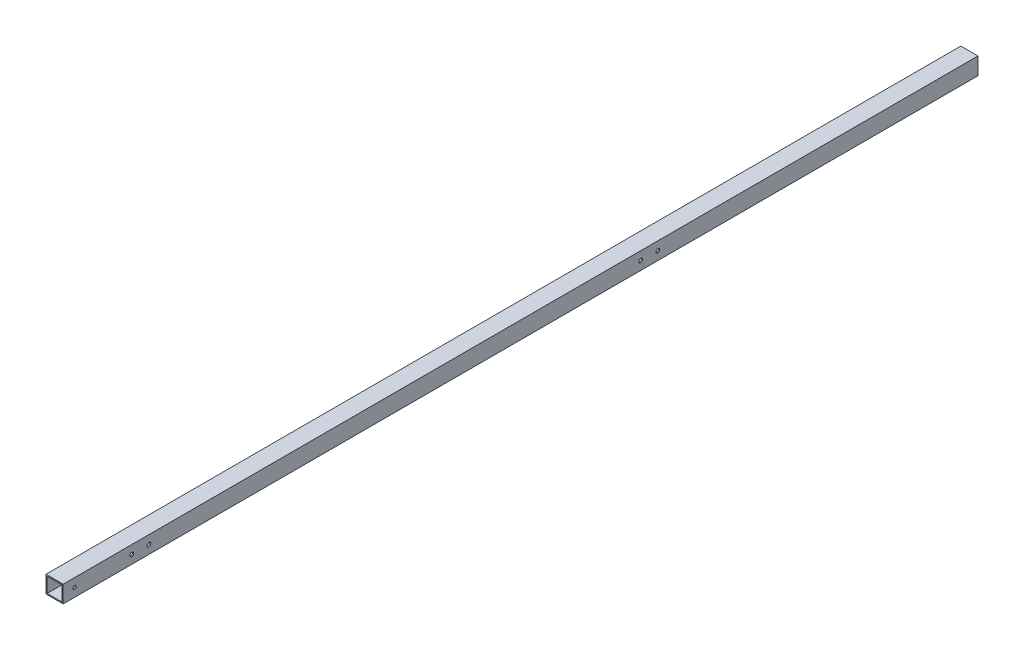
SolidWorks part; units mm, degrees
material "1060 合金"
ref_plane "前视基准面" through (0, 0, 0) normal (0, 0, 1) x (1, 0, 0)
ref_plane "上视基准面" through (0, 0, 0) normal (0, 1, 0) x (1, 0, 0)
ref_plane "右视基准面" through (0, 0, 0) normal (1, 0, 0) x (0, 0, -1)
other "Configuration Table"
sketch "草图1" plane through (0, 0, 0) normal (0, 0, 1) x (1, 0, 0)
  line L1 (0, 0) -> (15, 0)
  line L2 (0, 0) -> (0, -15)
  line L3 (0, -15) -> (15, -15)
  line L4 (15, 0) -> (15, -15)
  dimension "D1" = 15
  dimension "D2" = 15
extrude "拉伸-薄壁1" add sketch "草图1" along normal blind 800 thin
sketch "草图2" plane through (0, -15, 0) normal (0, -1, 0) x (1, 0, 0)
  circle A1 centre (7.5, 825) radius 2.6
  circle A2 centre (7.5, 825) radius 2.6
  dimension "D1" = 0
extrude "切除-拉伸1" [suppressed] cut sketch "草图2" against normal up to next
sketch "草图3" plane through (0, 0, 0) normal (-1, 0, 0) x (0, 0, 1)
  line L0 (800, 0) -> (0, 0) construction
  line L1 (0, 0) -> (0, -15) construction
  circle A0 centre (215, -7.5) radius 1.7
  circle A1 centre (170, -7.5) radius 1.7
  dimension "D1" = 3.4
  dimension "D2" = 3.4
  dimension "D3" = 45
  dimension "D4" = 7.5
  dimension "D5" = 7.5
  dimension "D6" = 170
sketch "草图4" plane through (15, 0, 0) normal (1, 0, 0) x (0, 0, -1)
  line L0 (-800, -15) -> (0, -15) construction
  line L1 (-800, -15) -> (-800, 0) construction
  circle A0 centre (-790, -7.5) radius 1.5
  dimension "D1" = 3
  dimension "D2" = 7.5
  dimension "D3" = 10
extrude "切除-拉伸3" cut sketch "草图4" against normal through all
sketch "草图5" plane through (15, 0, 0) normal (1, 0, 0) x (0, 0, -1)
  line L0 (-800, 0) -> (0, 0) construction
  line L1 (0, -15) -> (0, 0) construction
  line L2 (-800, -1) -> (-800, -14) construction
  circle A0 centre (-280, -7.5) radius 1.65
  circle A1 centre (-295, -7.5) radius 1.65
  circle A2 centre (-725, -7.5) radius 1.65
  circle A3 centre (-740, -7.5) radius 1.65
  dimension "D1" = 3.3
  dimension "D4" = 3.3
  dimension "D7" = 7.5
  dimension "D9" = 3.3
  dimension "D10" = 3.3
  dimension "D2" = 7.5
  dimension "D3" = 15
  dimension "D5" = 7.5
  dimension "D6" = 280
  dimension "D8" = 7.5
  dimension "D11" = 15
  dimension "D12" = 60
extrude "切除-拉伸4" cut sketch "草图5" against normal through all
